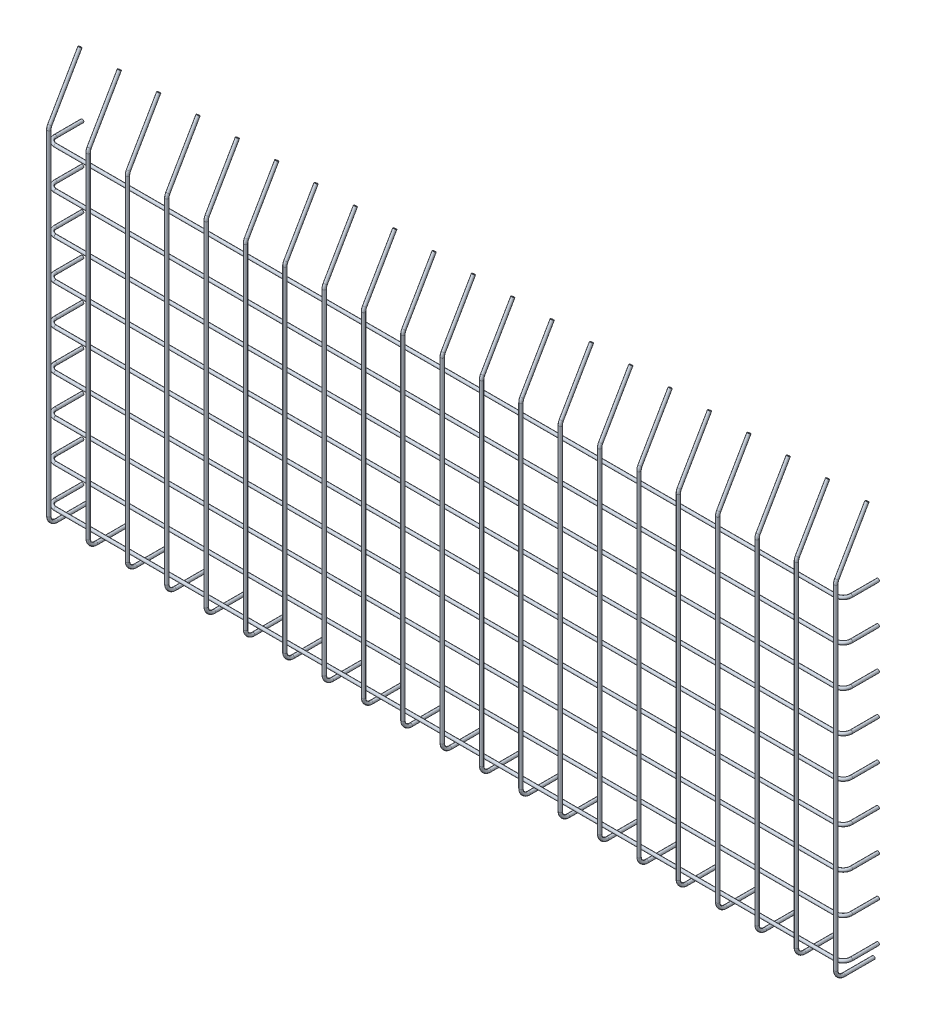
SolidWorks part; units mm, degrees
material "AISI 1020"
ref_plane "Спереди" through (0, 0, 0) normal (0, 0, 1) x (1, 0, 0)
ref_plane "Сверху" through (0, 0, 0) normal (0, 1, 0) x (1, 0, 0)
ref_plane "Справа" through (0, 0, 0) normal (1, 0, 0) x (0, 0, -1)
sketch "Эскиз1" plane through (0, 0, 0) normal (1, 0, 0) x (0, 0, -1)
  line L0 (50, 2) -> (12, 2)
  line L1 (50, -2375) -> (50, 451.425) construction
  line L2 (2, 12) -> (2, 436.8062)
  line L3 (3.3397, 441.8062) -> (41.6699, 508.196)
  line L4 (44.4019, 508.928) -> (22.4019, 470.8229) construction
  line L5 (0, -2375) -> (0, 480.2926) construction
  line L6 (47, 0) -> (3, 0) construction
  line L7 (-485, 812.269) -> (1294.1025, -214.8964) construction
  arc A0 (12, 2) -> (2, 12) centre (12, 12) cw
  arc A1 (2, 436.8062) -> (3.3397, 441.8062) centre (12, 436.8062) cw
  point P12 (0, 0)
  dimension "D4" = 10
  dimension "D1" = 2
  dimension "D2" = 2
  dimension "D3" = 2
sketch "Эскиз2" plane through (0, 0, -50) normal (0, 0, -1) x (-1, 0, 0)
  circle A0 centre (0, 2) radius 2
  dimension "D1" = 4
sweep "По траектории1" add profiles "Эскиз2" path "Эскиз1"
pattern_linear "Линейный массив1" count 11 spacing 50 along (1, 0, 0) of bodies 103
mirror "Зеркальное отражение1" about plane through (0, 0, 0) normal (1, 0, 0) of bodies 104 105 106 107 108 109 110 111 112 113
ref_plane "Плоскость1" through (0, 20, 0) normal (0, 1, 0) x (1, 0, 0)
sketch "Эскиз3" plane through (0, 20, 0) normal (0, 1, 0) x (1, 0, 0)
  line L0 (-505.5, 50) -> (-505.5, 16)
  line L1 (-495.5, 6) -> (495.5, 6)
  line L2 (505.5, 16) -> (505.5, 50)
  line L4 (-507.5, 48.5) -> (-507.5, 86.6051) construction
  line L5 (507.5, -484) -> (507.5, 1295.1025) construction
  line L6 (507.5, 50) -> (-507.5, 50) construction
  circle A0 centre (400, 2) radius 2 construction
  arc A1 (-505.5, 16) -> (-495.5, 6) centre (-495.5, 16) ccw
  arc A2 (495.5, 6) -> (505.5, 16) centre (495.5, 16) ccw
  point P4 (0, 0)
  point P5 (0, 0)
  point P17 (0, 0)
  dimension "D3" = 4
  dimension "D4" = 10
  dimension "D1" = 2
  dimension "D2" = 2
sketch "Эскиз4" plane through (0, 0, -50) normal (0, 0, -1) x (-1, 0, 0)
  circle A0 centre (505.5, 20) radius 2
  dimension "D1" = 4
sweep "По траектории2" add profiles "Эскиз4" path "Эскиз3"
pattern_linear "Линейный массив3" count 9 spacing 50 along (0, 1, 0) of bodies 124
